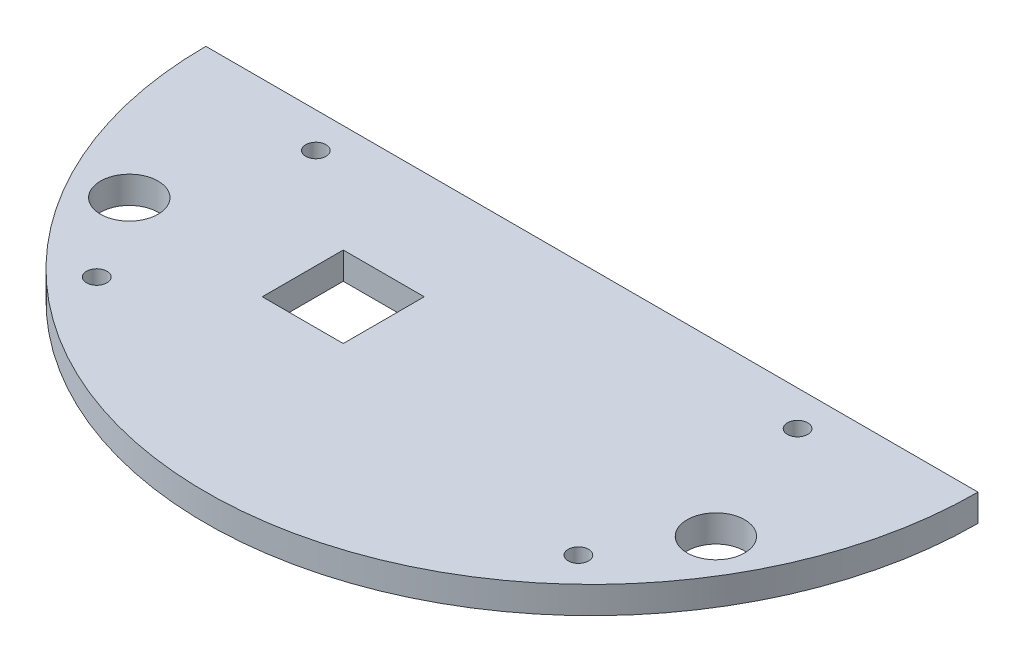
SolidWorks part; units mm, degrees
ref_plane "Plan de face" through (0, 0, 0) normal (0, 0, 1) x (1, 0, 0)
ref_plane "Plan de dessus" through (0, 0, 0) normal (0, 1, 0) x (1, 0, 0)
ref_plane "Plan de droite" through (0, 0, 0) normal (1, 0, 0) x (0, 0, -1)
sketch "Esquisse1" plane through (0, 0, 0) normal (0, 1, 0) x (1, 0, 0)
  line L0 (-57, 0) -> (57, 0)
  line L1 (0, -22.5) -> (0, 0) construction
  line L2 (-31.25, -10) -> (31.25, -10)
  line L3 (-31.25, -10) -> (-31.25, -35)
  line L4 (-31.25, -35) -> (31.25, -35)
  line L5 (31.25, -10) -> (31.25, -35)
  line L6 (-31.25, -10) -> (31.25, -35) construction
  line L7 (-31.25, -35) -> (31.25, -10) construction
  line L8 (-43.3013, -25) -> (0, 0) construction
  line L9 (0, 0) -> (43.3013, -25) construction
  line L10 (43.3013, -25) -> (-43.3013, -25) construction
  line L12 (-31.25, -35) -> (0.75, -35) construction
  line L13 (-31.25, -35) -> (-31.25, -43.6) construction
  line L14 (-31.25, -43.6) -> (0.75, -43.6) construction
  line L15 (0.75, -35) -> (0.75, -43.6) construction
  line L16 (-31.25, -35) -> (0.75, -43.6) construction
  line L17 (-31.25, -43.6) -> (0.75, -35) construction
  arc A0 (-57, 0) -> (57, 0) centre (0, 0) ccw
  circle A1 centre (-43.3013, -25) radius 4.25
  circle A2 centre (43.3013, -25) radius 4.25
  point P4 (0, -22.5)
  point P16 (-15.25, -39.3)
  dimension "D1" = 57
  dimension "D6" = 8.5
  dimension "D2" = 25
  dimension "D3" = 62.5
  dimension "D4" = 50
  dimension "D5" = 120
  dimension "D7" = 8.6
  dimension "D8" = 32
  dimension "D9" = 22.5
extrude "Boss.-Extru.1" add sketch "Esquisse1" along normal blind 4
sketch "Esquisse2" plane through (0, 4, 0) normal (0, 1, 0) x (1, 0, 0)
  line L0 (0, -21.3765) -> (0, 0) construction
  line L1 (35.5571, -37.5546) -> (-35.5571, -37.5546) construction
  line L2 (35.5571, -37.5546) -> (35.5571, -5.1985) construction
  line L3 (35.5571, -5.1985) -> (-35.5571, -5.1985) construction
  line L4 (-35.5571, -37.5546) -> (-35.5571, -5.1985) construction
  line L5 (35.5571, -37.5546) -> (-35.5571, -5.1985) construction
  line L6 (35.5571, -5.1985) -> (-35.5571, -37.5546) construction
  circle A0 centre (-35.5571, -37.5546) radius 5 construction
  circle A1 centre (-35.5571, -37.5546) radius 1.5
  circle A2 centre (-35.5571, -5.1985) radius 5 construction
  circle A3 centre (-35.5571, -5.1985) radius 1.5
  circle A4 centre (35.5571, -5.1985) radius 1.5
  circle A5 centre (35.5571, -37.5546) radius 1.5
  point P0 (0, -21.3765)
  dimension "D1" = 10
  dimension "D2" = 3
  dimension "D3" = 3
  dimension "D4" = 10
  dimension "D5" = 3
  dimension "D6" = 3
  dimension "D7" = 5.1985
  dimension "D8" = 37.5546
  dimension "D9" = 35.5571
extrude "Enlèv. mat.-Extru.1" cut sketch "Esquisse2" against normal through all
sketch "Esquisse3" plane through (0, 4, 0) normal (0, 1, 0) x (1, 0, 0)
  line L1 (-33.0434, -8.9045) -> (33.0434, -8.9045)
  line L2 (-33.0434, -8.9045) -> (-33.0434, -36.8249)
  line L3 (-33.0434, -36.8249) -> (33.0434, -36.8249)
  line L4 (33.0434, -8.9045) -> (33.0434, -36.8249)
  point P6 (0, 0)
  point P7 (0, 0)
  point P8 (0, 0)
  point P9 (33.0434, -36.8249)
  point P10 (0, 0)
  point P11 (-33.0434, -8.9045)
extrude "Boss.-Extru.2" add sketch "Esquisse3" against normal blind 4
sketch "Esquisse5" plane through (0, 4, 0) normal (0, 1, 0) x (1, 0, 0)
  line L1 (-20.8143, -27.8589) -> (-8.8561, -27.8589)
  line L2 (-20.8143, -27.8589) -> (-20.8143, -15.9007)
  line L3 (-20.8143, -15.9007) -> (-8.8561, -15.9007)
  line L4 (-8.8561, -27.8589) -> (-8.8561, -15.9007)
  line L5 (-20.8143, -27.8589) -> (-8.8561, -15.9007) construction
  line L6 (-20.8143, -15.9007) -> (-8.8561, -27.8589) construction
  spline S0 degree 3 poles (-14.8819, -14.8169) (-14.5816, -14.8169) (-13.9906, -14.8168) (-13.2503, -14.8171) (-12.6638, -14.8164) (-12.2099, -14.8179) (-11.7509, -14.8138) (-11.0788, -14.8278) (-10.2165, -15.0153) (-9.4791, -15.4002) (-9.0215, -15.7498) (-8.7709, -15.9752) (-8.53, -16.2318) (-8.3052, -16.5196) (-8.0989, -16.8368) (-7.986, -17.0668) (-7.9287, -17.1836) knots 0 0 0 0 0.11406 0.224497 0.281236 0.33684 0.39692 0.455587 0.59201 0.727854 0.768618 0.811528 0.856264 0.902637 0.950555 1 1 1 1 construction
  point P0 (-14.8352, -21.8798)
extrude "Enlèv. mat.-Extru.2" cut sketch "Esquisse5" against normal through all
